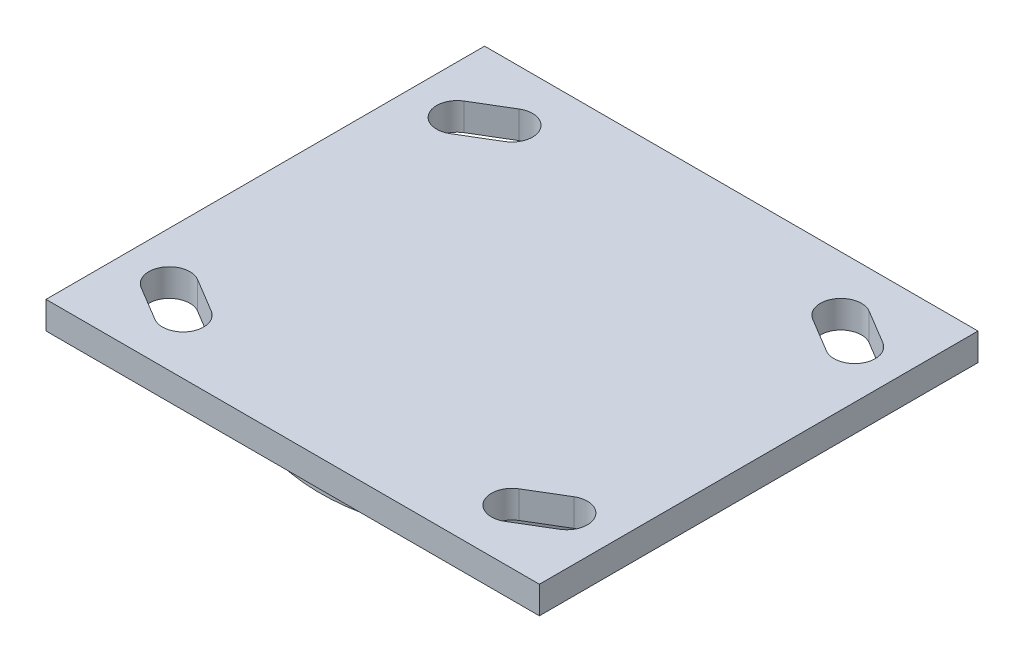
SolidWorks part; units mm, degrees
ref_plane "Front Plane" through (0, 0, 0) normal (0, 0, 1) x (1, 0, 0)
ref_plane "Top Plane" through (0, 0, 0) normal (0, 1, 0) x (1, 0, 0)
ref_plane "Right Plane" through (0, 0, 0) normal (1, 0, 0) x (0, 0, -1)
sketch "Sketch1" plane through (0, 0, 0) normal (0, 0, 1) x (1, 0, 0)
  line L1 (-57.15, 0) -> (57.15, 0)
  line L2 (-57.15, 0) -> (-57.15, -6.35)
  line L3 (-57.15, -6.35) -> (57.15, -6.35)
  line L4 (57.15, 0) -> (57.15, -6.35)
  dimension "Plate Length" = 114.3
  dimension "Plate Thickness" = 6.35
extrude "Boss-Extrude1" add sketch "Sketch1" along normal mid plane 101.6
sketch "Sketch2" plane through (0, 0, 0) normal (0, 1, 0) x (1, 0, 0)
  line L0 (-38.1, 38.1) -> (-46.0375, 33.3375) construction
  line L1 (-35.6497, 34.0162) -> (-43.5872, 29.2537)
  line L2 (-40.5503, 42.1838) -> (-48.4878, 37.4213)
  line L3 (0, 0) -> (0, 50.8) construction
  line L4 (0, 0) -> (57.15, 0) construction
  line L5 (57.15, -50.8) -> (57.15, 50.8) construction
  line L6 (57.15, 50.8) -> (-57.15, 50.8) construction
  line L7 (-38.1, -38.1) -> (-46.0375, -33.3375) construction
  line L8 (-35.6497, -34.0162) -> (-43.5872, -29.2537)
  line L9 (-40.5503, -42.1838) -> (-48.4878, -37.4213)
  line L10 (38.1, 38.1) -> (46.0375, 33.3375) construction
  line L11 (35.6497, 34.0162) -> (43.5872, 29.2537)
  line L12 (40.5503, 42.1838) -> (48.4878, 37.4213)
  line L13 (38.1, -38.1) -> (46.0375, -33.3375) construction
  line L14 (35.6497, -34.0162) -> (43.5872, -29.2537)
  line L15 (40.5503, -42.1838) -> (48.4878, -37.4213)
  arc A0 (-35.6497, 34.0162) -> (-40.5503, 42.1838) centre (-38.1, 38.1) ccw
  arc A1 (-48.4878, 37.4213) -> (-43.5872, 29.2537) centre (-46.0375, 33.3375) ccw
  arc A2 (-35.6497, -34.0162) -> (-40.5503, -42.1838) centre (-38.1, -38.1) cw
  arc A3 (-48.4878, -37.4213) -> (-43.5872, -29.2537) centre (-46.0375, -33.3375) cw
  arc A4 (35.6497, 34.0162) -> (40.5503, 42.1838) centre (38.1, 38.1) cw
  arc A5 (48.4878, 37.4213) -> (43.5872, 29.2537) centre (46.0375, 33.3375) cw
  arc A6 (35.6497, -34.0162) -> (40.5503, -42.1838) centre (38.1, -38.1) ccw
  arc A7 (48.4878, -37.4213) -> (43.5872, -29.2537) centre (46.0375, -33.3375) ccw
  point P2 (-42.0687, 35.7188)
  point P17 (-42.0687, -35.7188)
  point P24 (42.0688, 35.7188)
  point P31 (42.0687, -35.7187)
  dimension "D3" = 92.075
  dimension "D5" = 76.2
  dimension "D1" = 9.525
  dimension "D2" = 76.2
  dimension "D4" = 66.675
extrude "1-2 holes" cut sketch "Sketch2" against normal through all
sketch "Sketch3" plane through (0, 0, 0) normal (0, 1, 0) x (1, 0, 0)
  line L0 (0, 0) -> (0, 50.8) construction
  line L1 (57.15, 50.8) -> (-57.15, 50.8) construction
  line L2 (0, 0) -> (57.15, 0) construction
  line L3 (57.15, -50.8) -> (57.15, 50.8) construction
  circle A0 centre (-57.15, 52.3875) radius 4.7625
  circle A1 centre (57.15, 52.3875) radius 4.7625
  circle A2 centre (57.15, -52.3875) radius 4.7625
  circle A3 centre (-57.15, -52.3875) radius 4.7625
  dimension "D1" = 9.525
  dimension "D2" = 114.3
  dimension "D3" = 104.775
extrude "3-holes" [suppressed] cut sketch "Sketch3" against normal through all
sketch "Sketch4" plane through (0, 0, 0) normal (0, 0, 1) x (1, 0, 0)
  line L0 (0, -6.35) -> (0, -27.1526) construction
  line L1 (0, -27.1526) -> (43.18, -27.1526)
  line L2 (43.18, -27.1526) -> (43.18, -16.0401)
  line L3 (43.18, -16.0401) -> (40.64, -16.0401)
  line L4 (40.64, -16.0401) -> (40.64, -13.5001)
  line L5 (40.64, -13.5001) -> (44.45, -13.5001)
  line L6 (44.45, -13.5001) -> (44.45, -6.35)
  line L7 (44.45, -6.35) -> (0, -6.35)
  line L8 (-57.15, -6.35) -> (57.15, -6.35) construction
  line L9 (0, -6.35) -> (0, -27.1526)
  line L10 (-91.9657, -138.3203) -> (-29.172, -27.1526) construction
  line L11 (-47.7343, -163.3047) -> (29.172, -27.1526) construction
  line L12 (-69.85, -150.8125) -> (0, -27.1526) construction
  line L13 (0, 0) -> (0, -252.4125) construction
  line L14 (57.15, 0) -> (-57.15, 0) construction
  circle A0 centre (-69.85, -150.8125) radius 101.6 construction
  arc A1 (-91.9657, -138.3203) -> (-47.7343, -163.3047) centre (-69.85, -150.8125) ccw construction
  point P13 (-69.85, -49.2125)
  point P14 (-69.85, -252.4125)
  dimension "Wheel Dia" = 203.2
  dimension "D7" = 50.8
  dimension "Mount Height" = 252.4125
  dimension "Offset" = 69.85
  dimension "D1" = 7.1501
  dimension "D2" = 11.1125
  dimension "D3" = 2.54
  dimension "D4" = 88.9
  dimension "D5" = 86.36
  dimension "D6" = 81.28
revolve "Revolve1" add sketch "Sketch4" angle 360 about L0
ref_plane "Plane1" through (-69.85, 0, 0) normal (1, 0, 0) x (0, 0, -1)
sketch "Sketch5" plane through (-69.85, 0, 0) normal (1, 0, 0) x (0, 0, -1)
  line L1 (-35.56, -49.2125) -> (35.56, -49.2125)
  line L2 (-35.56, -49.2125) -> (-35.56, -252.4125)
  line L3 (-35.56, -252.4125) -> (35.56, -252.4125)
  line L4 (35.56, -49.2125) -> (35.56, -252.4125)
  dimension "Wheel Width" = 71.12
sketch "Sketch6" plane through (-69.85, 0, 0) normal (1, 0, 0) x (0, 0, -1)
  line L0 (-35.56, -89.8525) -> (-35.56, -62.1434)
  line L1 (-22.6291, -49.2125) -> (-19.8005, -49.2125)
  line L2 (35.56, -62.1434) -> (35.56, -89.8525)
  line L3 (-35.56, -49.2125) -> (35.56, -49.2125) construction
  line L4 (-35.56, -49.2125) -> (-35.56, -252.4125) construction
  line L5 (35.56, -49.2125) -> (35.56, -252.4125) construction
  line L6 (-111.1453, -150.8125) -> (111.1453, -150.8125) construction
  line L7 (-35.56, -89.8525) -> (-36.83, -89.8525)
  line L8 (-36.83, -89.8525) -> (-36.83, -92.3925)
  line L9 (-36.83, -130.175) -> (-40.005, -130.175)
  line L10 (-40.005, -130.175) -> (-40.005, -150.8125)
  line L11 (0, -49.2125) -> (0, -256.5466) construction
  line L12 (0, -49.2125) -> (0, -252.4125) construction
  line L13 (40.005, -130.175) -> (40.005, -150.8125)
  line L14 (36.83, -130.175) -> (40.005, -130.175)
  line L17 (-40.005, -150.8125) -> (40.005, -150.8125)
  line L18 (-19.8005, -49.2125) -> (-19.8005, -51.5937)
  line L19 (-19.8005, -51.5937) -> (-14.1432, -51.5937)
  line L20 (-14.1432, -51.5937) -> (-14.1432, -49.2125)
  line L21 (-8.4859, -49.2125) -> (-8.4859, -51.5937)
  line L22 (-8.4859, -51.5937) -> (-2.8286, -51.5937)
  line L23 (-2.8286, -51.5937) -> (-2.8286, -49.2125)
  line L24 (2.8286, -51.5937) -> (2.8286, -49.2125)
  line L25 (8.4859, -51.5937) -> (2.8286, -51.5937)
  line L26 (8.4859, -49.2125) -> (8.4859, -51.5937)
  line L27 (14.1432, -51.5937) -> (14.1432, -49.2125)
  line L28 (19.8005, -51.5937) -> (14.1432, -51.5937)
  line L29 (19.8005, -49.2125) -> (19.8005, -51.5937)
  line L30 (-14.1432, -49.2125) -> (-8.4859, -49.2125)
  line L31 (-2.8286, -49.2125) -> (2.8286, -49.2125)
  line L32 (8.4859, -49.2125) -> (14.1432, -49.2125)
  line L33 (19.8005, -49.2125) -> (22.6291, -49.2125)
  line L34 (-36.83, -92.3925) -> (-33.655, -92.3925)
  line L35 (-21.5084, -105.0683) -> (-5.4383, -106.4743)
  line L36 (-2.54, -109.6372) -> (-2.54, -130.175)
  line L37 (-27.305, -98.7425) -> (-27.305, -208.9815) construction
  line L38 (-36.83, -130.175) -> (-2.54, -130.175)
  line L39 (36.83, -130.175) -> (2.54, -130.175)
  line L40 (2.54, -109.6372) -> (2.54, -130.175)
  line L41 (21.5084, -105.0683) -> (5.4383, -106.4743)
  line L42 (36.83, -92.3925) -> (33.655, -92.3925)
  line L43 (36.83, -89.8525) -> (36.83, -92.3925)
  line L44 (35.56, -89.8525) -> (36.83, -89.8525)
  arc A0 (-35.56, -62.1434) -> (-22.6291, -49.2125) centre (-22.6291, -62.1434) cw
  arc A1 (22.6291, -49.2125) -> (35.56, -62.1434) centre (22.6291, -62.1434) cw
  arc A2 (-33.655, -92.3925) -> (-27.305, -98.7425) centre (-33.655, -98.7425) cw
  arc A3 (-27.305, -98.7425) -> (-21.5084, -105.0683) centre (-20.955, -98.7425) ccw
  arc A4 (-5.4383, -106.4743) -> (-2.54, -109.6372) centre (-5.715, -109.6372) cw
  arc A5 (5.4383, -106.4743) -> (2.54, -109.6372) centre (5.715, -109.6372) ccw
  arc A6 (27.305, -98.7425) -> (21.5084, -105.0683) centre (20.955, -98.7425) cw
  arc A7 (33.655, -92.3925) -> (27.305, -98.7425) centre (33.655, -98.7425) ccw
  dimension "D1" = 12.9309
  dimension "D13" = 6.35
  dimension "D16" = 3.175
  dimension "D2" = 1.27
  dimension "D3" = 3.175
  dimension "D4" = 41.275
  dimension "D5" = 121.92
  dimension "D6" = 45.2582
  dimension "D7" = 5.6573
  dimension "D8" = 2.3813
  dimension "D9" = 5.6573
  dimension "D10" = 2.8286
  dimension "D11" = 3.175
  dimension "D12" = 2.54
  dimension "D14" = 5
  dimension "D15" = 2.54
revolve "Revolve2" add sketch "Sketch6" angle 360 about L6
sketch "Sketch13" plane through (0, 0, 2.54) normal (0, 0, 1) x (1, 0, 0)
  line L0 (-69.85, -130.175) -> (-69.85, -109.6372) construction
  line L1 (-69.85, -150.8125) -> (-98.9653, -121.6972) construction
  line L2 (-69.85, -150.8125) -> (-60.3899, -150.8125) construction
  circle A0 centre (-69.85, -150.8125) radius 41.1753 construction
  circle A1 centre (-69.85, -150.8125) radius 20.6375
  circle A2 centre (-69.85, -150.8125) radius 20.6375 construction
  circle A4 centre (-69.85, -150.8125) radius 41.1753 construction
  circle A6 centre (-69.85, -150.8125) radius 27.4834 construction
  circle A7 centre (-69.85, -150.8125) radius 34.3294 construction
  arc A8 (-101.0418, -136.4746) -> (-84.1879, -119.6207) centre (-90.1989, -130.4636) cw
  arc A9 (-84.1879, -119.6207) -> (-55.5121, -119.6207) centre (-69.85, -93.7572) ccw
  arc A10 (-55.5121, -119.6207) -> (-38.6582, -136.4746) centre (-49.5011, -130.4636) cw
  arc A11 (-101.0418, -136.4746) -> (-101.0418, -165.1504) centre (-126.9053, -150.8125) cw
  arc A12 (-38.6582, -136.4746) -> (-38.6582, -165.1504) centre (-12.7947, -150.8125) ccw
  arc A13 (-101.0418, -165.1504) -> (-84.1879, -182.0043) centre (-90.1989, -171.1614) ccw
  arc A15 (-55.5121, -182.0043) -> (-38.6582, -165.1504) centre (-49.5011, -171.1614) ccw
  arc A16 (-84.1879, -182.0043) -> (-55.5121, -182.0043) centre (-69.85, -207.8678) cw
  point P8 (-69.85, -123.3291)
  point P9 (-69.85, -116.4831)
  dimension "D2" = 20.5378
  dimension "D3" = 6.8459
  dimension "D4" = 6.8459
  dimension "D5" = 45
  dimension "D1" = 0
extrude "Boss-Extrude5" add sketch "Sketch13" along normal blind 6.35
sketch "Sketch14" plane through (0, 0, 8.89) normal (0, 0, 1) x (1, 0, 0)
  line L0 (-69.85, -150.8125) -> (-98.9653, -121.6972) construction
  line L1 (-94.1245, -132.0372) -> (-89.362, -129.2876)
  line L2 (-89.362, -129.2876) -> (-89.362, -123.7883)
  line L3 (-89.362, -123.7883) -> (-94.1245, -121.0387)
  line L4 (-94.1245, -121.0387) -> (-98.887, -123.7883)
  line L5 (-98.887, -123.7883) -> (-98.887, -129.2876)
  line L6 (-98.887, -129.2876) -> (-94.1245, -132.0372)
  line L7 (-69.85, -150.8125) -> (-69.85, -136.2548) construction
  line L8 (-69.85, -150.8125) -> (-63.5, -150.8125) construction
  line L9 (-40.813, -129.2876) -> (-45.5755, -132.0372)
  line L10 (-40.813, -123.7883) -> (-40.813, -129.2876)
  line L11 (-45.5755, -121.0387) -> (-40.813, -123.7883)
  line L12 (-50.338, -123.7883) -> (-45.5755, -121.0387)
  line L13 (-50.338, -129.2876) -> (-50.338, -123.7883)
  line L14 (-45.5755, -132.0372) -> (-50.338, -129.2876)
  line L15 (-45.5755, -169.5878) -> (-50.338, -172.3374)
  line L16 (-50.338, -172.3374) -> (-50.338, -177.8367)
  line L17 (-50.338, -177.8367) -> (-45.5755, -180.5863)
  line L18 (-45.5755, -180.5863) -> (-40.813, -177.8367)
  line L19 (-40.813, -177.8367) -> (-40.813, -172.3374)
  line L20 (-40.813, -172.3374) -> (-45.5755, -169.5878)
  line L21 (-98.887, -172.3374) -> (-94.1245, -169.5878)
  line L22 (-98.887, -177.8367) -> (-98.887, -172.3374)
  line L23 (-94.1245, -180.5863) -> (-98.887, -177.8367)
  line L24 (-89.362, -177.8367) -> (-94.1245, -180.5863)
  line L25 (-89.362, -172.3374) -> (-89.362, -177.8367)
  line L26 (-94.1245, -169.5878) -> (-89.362, -172.3374)
  circle A0 centre (-94.1245, -126.538) radius 4.7625 construction
  circle A1 centre (-69.85, -150.8125) radius 34.3294 construction
  circle A3 centre (-45.5755, -126.538) radius 4.7625 construction
  circle A4 centre (-45.5755, -175.087) radius 4.7625 construction
  circle A5 centre (-94.1245, -175.087) radius 4.7625 construction
  dimension "D1" = 9.525
extrude "Boss-Extrude6" add sketch "Sketch14" along normal blind 4.7625
sketch "Sketch15" plane through (0, 0, 13.6525) normal (0, 0, 1) x (1, 0, 0)
  circle A0 centre (-94.1245, -126.538) radius 3.9687
  circle A1 centre (-45.5755, -126.538) radius 3.9687
  circle A2 centre (-94.1245, -175.087) radius 3.9687
  circle A3 centre (-45.5755, -175.087) radius 3.9687
  dimension "D1" = 7.9375
extrude "Boss-Extrude7" add sketch "Sketch15" along normal blind 2.54
sketch "Sketch16" plane through (0, 0, -2.54) normal (0, 0, -1) x (-1, 0, 0)
  circle A0 centre (45.5755, -126.538) radius 6.35
  circle A1 centre (94.1245, -126.538) radius 6.35
  circle A2 centre (94.1245, -175.087) radius 6.35
  circle A3 centre (45.5755, -175.087) radius 6.35
  dimension "D1" = 12.7
extrude "Boss-Extrude8" add sketch "Sketch16" along normal blind 4.7625
sketch "Sketch7" plane through (0, -27.1526, 0) normal (0, -1, 0) x (1, 0, 0)
  line L0 (-49.2125, 40.005) -> (-90.4875, 40.005) construction
  line L1 (-171.45, 48.895) -> (29.172, 48.895)
  line L2 (-171.45, 48.895) -> (-171.45, -48.895)
  line L3 (-171.45, -48.895) -> (29.172, -48.895)
  line L4 (29.172, 48.895) -> (29.172, -48.895)
  line L6 (-171.45, 14.1432) -> (-171.45, 8.4859) construction
  line L8 (29.172, -48.895) -> (29.172, 48.895) construction
  line L9 (-29.172, 48.895) -> (-29.172, -48.895) construction
  line L14 (-29.172, 31.8356) -> (29.172, 31.8356) construction
  line L15 (-29.172, 31.8356) -> (-29.172, 25.4856) construction
  line L16 (-29.172, 25.4856) -> (29.172, 25.4856) construction
  line L17 (29.172, 31.8356) -> (29.172, 25.4856) construction
  line L18 (-29.172, -25.4856) -> (29.172, -25.4856) construction
  line L19 (-29.172, -25.4856) -> (-29.172, -31.8356) construction
  line L20 (-29.172, -31.8356) -> (29.172, -31.8356) construction
  line L21 (29.172, -25.4856) -> (29.172, -31.8356) construction
  circle A0 centre (0, 0) radius 43.18 construction
  circle A1 centre (0, 0) radius 43.18 construction
  dimension "D1" = 8.89
  dimension "D3" = 6.35
extrude "Boss-Extrude2" add sketch "Sketch7" along normal up to vertex (225.2599 mm away) separate body up to point (-69.85, -252.4125, -35.56)
sketch "Sketch8" plane through (0, 0, 48.895) normal (0, 0, 1) x (1, 0, 0)
  line L0 (-91.9657, -138.3203) -> (-29.172, -27.1526) construction
  line L1 (-47.7343, -163.3047) -> (29.172, -27.1526) construction
  line L2 (-91.9657, -138.3203) -> (-29.172, -27.1526)
  line L3 (-47.7343, -163.3047) -> (29.172, -27.1526)
  arc A0 (-91.9657, -138.3203) -> (-47.7343, -163.3047) centre (-69.85, -150.8125) ccw construction
  arc A1 (-91.9657, -138.3203) -> (-47.7343, -163.3047) centre (-69.85, -150.8125) ccw
extrude "Cut-Extrude1" cut sketch "Sketch8" against normal through all and the other way through all flip side to cut
sketch "Sketch9" plane through (0, -144.3067, 0) normal (-1, 0, 0) x (0, 0, -1)
  line L0 (48.895, 108.1058) -> (48.895, -95.0942)
  line L2 (48.895, -117.1541) -> (-48.895, -117.1541) construction
  line L3 (25.4856, -117.1541) -> (42.545, -95.0942)
  line L4 (25.4856, -117.1541) -> (31.8356, -117.1541) construction
  line L5 (42.545, -95.0942) -> (42.545, 108.1058)
  line L6 (48.895, 108.1058) -> (42.545, 108.1058)
  line L7 (48.895, -117.1541) -> (48.895, 18.998) construction
  line L8 (-35.56, 108.1058) -> (35.56, 108.1058) construction
  line L9 (48.895, -95.0942) -> (31.8356, -117.1541)
  line L10 (25.4856, -117.1541) -> (31.8356, -117.1541)
  line L11 (0, -144.3067) -> (0, 108.1058) construction
  line L12 (-25.4856, -117.1541) -> (-31.8356, -117.1541)
  line L13 (-48.895, -95.0942) -> (-31.8356, -117.1541)
  line L14 (-48.895, 108.1058) -> (-42.545, 108.1058)
  line L15 (-42.545, -95.0942) -> (-42.545, 108.1058)
  line L16 (-25.4856, -117.1541) -> (-42.545, -95.0942)
  line L17 (-48.895, 108.1058) -> (-48.895, -95.0942)
  dimension "D1" = 6.35
  dimension "D2" = 6.35
extrude "Cut-Extrude3" cut sketch "Sketch9" against normal through all and the other way through all flip side to cut
sketch "Sketch10" plane through (0, 0, 48.895) normal (0, 0, 1) x (1, 0, 0)
  line L1 (-69.85, -137.9809) -> (-80.9625, -144.3967)
  line L2 (-80.9625, -144.3967) -> (-80.9625, -157.2283)
  line L3 (-80.9625, -157.2283) -> (-69.85, -163.6441)
  line L4 (-69.85, -163.6441) -> (-58.7375, -157.2283)
  line L5 (-58.7375, -157.2283) -> (-58.7375, -144.3967)
  line L6 (-58.7375, -144.3967) -> (-69.85, -137.9809)
  circle A0 centre (-69.85, -150.8125) radius 11.1125 construction
  dimension "D1" = 22.225
extrude "Boss-Extrude3" add sketch "Sketch10" along normal blind 7.9375 separate body
sketch "Sketch11" plane through (0, 0, 56.8325) normal (0, 0, 1) x (1, 0, 0)
  circle A0 centre (-69.85, -150.8125) radius 11.1125 construction
  circle A1 centre (-69.85, -150.8125) radius 11.1125
extrude "Cut-Extrude4" cut sketch "Sketch11" against normal through all draft 60 flip side to cut
mirror "Mirror1" about plane through (0, 0, 0) normal (0, 0, 1) of bodies 113
sketch "Sketch12" plane through (0, 0, -42.545) normal (0, 0, 1) x (1, 0, 0)
  circle A0 centre (-69.85, -150.8125) radius 10.795
  dimension "D1" = 21.59
extrude "Boss-Extrude4" add sketch "Sketch12" along normal up to surface (85.09 mm away)
combine bodies "Combine1" operation type add bodies to combine 115 114 113 104 102
sketch "Sketch17" plane through (0, -13.5001, 0) normal (0, -1, 0) x (1, 0, 0)
  circle A0 centre (0, 0) radius 1440.18
  arc A1 (29.172, 31.8356) -> (-29.172, 31.8356) centre (0, 0) ccw construction
  dimension "D1" = 1397
extrude "Cut-Extrude5" cut sketch "Sketch17" along normal blind 1397
equation "\"D5@Sketch6\" = \"Wheel Dia@Sketch4\"*.6"
equation "\"D1@Sketch6\" = \"Wheel Width@Sketch5\"/5.5"
equation "\"D7@Sketch6\" = \"D6@Sketch6\"/8"
equation "\"D9@Sketch6\" = \"D7@Sketch6\""
equation "\"D10@Sketch6\" = \"D7@Sketch6\"/2"
equation "\"D3@Sketch13\" = \"D2@Sketch13\"/3"
equation "\"D4@Sketch13\" = \"D3@Sketch13\""
